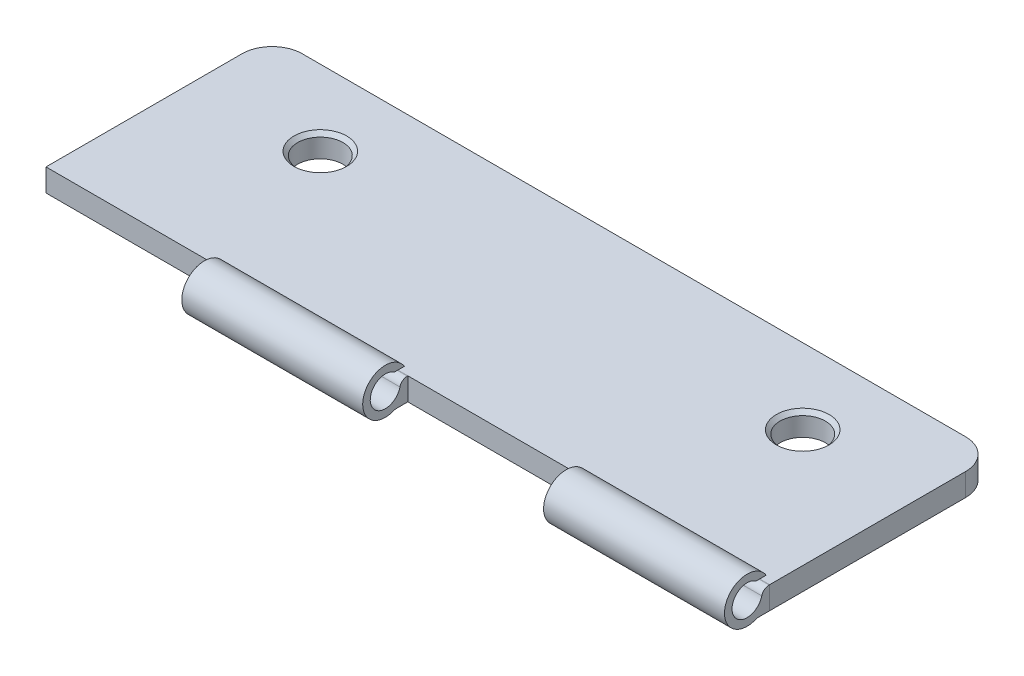
SolidWorks part; units mm, degrees
ref_plane "Front Plane" through (0, 0, 0) normal (0, 0, 1) x (1, 0, 0)
ref_plane "Top Plane" through (0, 0, 0) normal (0, 1, 0) x (1, 0, 0)
ref_plane "Right Plane" through (0, 0, 0) normal (1, 0, 0) x (0, 0, -1)
sketch "Sketch1" plane through (0, 0, 0) normal (0, 1, 0) x (1, 0, 0)
  line L1 (-24, -7.5) -> (24, -7.5)
  line L2 (-24, -7.5) -> (-24, 5.5)
  line L3 (-22, 7.5) -> (22, 7.5)
  line L4 (24, -7.5) -> (24, 5.5)
  line L5 (-24, -7.5) -> (24, 7.5) construction
  line L6 (-24, 7.5) -> (24, -7.5) construction
  circle A0 centre (-15.8035, 2.5) radius 1.5
  circle A1 centre (16.1965, 2.5) radius 1.5
  arc A2 (22, 7.5) -> (24, 5.5) centre (22, 5.5) cw
  arc A3 (-24, 5.5) -> (-22, 7.5) centre (-22, 5.5) cw
  point P0 (0, 0)
  dimension "D1" = 32
  dimension "D2" = 3
  dimension "D3" = 3
  dimension "D4" = 16
  dimension "D5" = 15
  dimension "D7" = 2
  dimension "D8" = 10
  dimension "D6" = 48
extrude "Boss-Extrude1" add sketch "Sketch1" along normal blind 1.5
sketch "Sketch2" plane through (24, 0, 0) normal (1, 0, 0) x (0, 0, -1)
  line L0 (-8.3986, 2.1577) -> (-7.7267, 2.1577)
  line L1 (-7.5, 0) -> (-8.2412, 0)
  line L2 (-7.5, 0) -> (-7.5, 1.5)
  line L3 (-7.5, 1.5) -> (-7.535, 1.5)
  arc A0 (-7.7267, 2.1577) -> (-8.4291, -0.0367) centre (-8.9928, 1.3534) ccw
  arc A1 (-8.3986, 2.1577) -> (-8.021, 1.1178) centre (-8.9928, 1.3534) ccw
  arc A2 (-7.5, 1.2068) -> (-7.5, 1.5) centre (-8.9928, 1.3534) ccw
  arc A3 (-8.2412, 0) -> (-8.4291, -0.0367) centre (-8.2412, -0.5) ccw
  arc A4 (-7.535, 1.5) -> (-8.021, 1.1178) centre (-7.535, 1) ccw
  line M12 (-7.5, 1.5) -> (-7.5, 0)
  dimension "D1" = 3
  dimension "D2" = 2
  dimension "D3" = 0.5
extrude "Boss-Extrude2" add sketch "Sketch2" against normal blind 12 separate body contours L3 A4 A1 L0 A0 A3 L1 L2 M12
pattern_linear "LPattern1" count 2 spacing 24 along (-1, 0, 0) of "Boss-Extrude2"
chamfer "Chamfer1" distance 0.25 angle 45 2 edges at (16.1965, 1.5, -1) (-15.8035, 1.5, -1)
